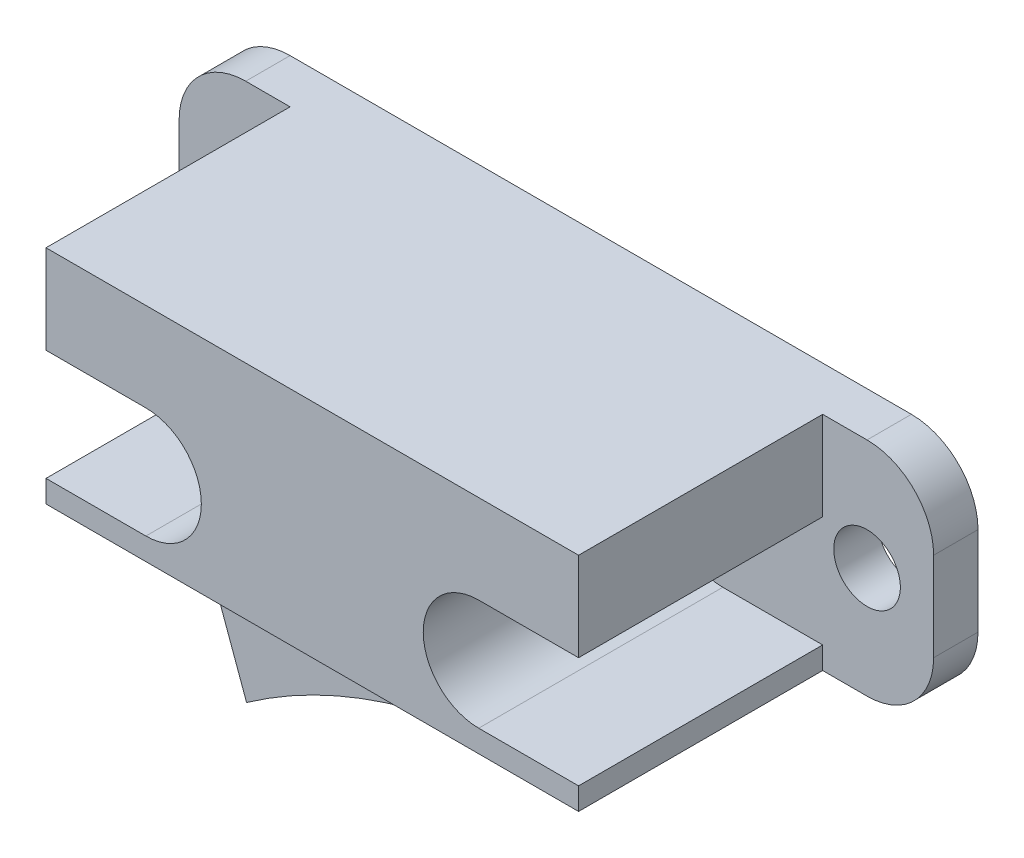
SolidWorks part; units mm, degrees
ref_plane "前视基准面" through (0, 0, 0) normal (0, 0, 1) x (1, 0, 0)
ref_plane "上视基准面" through (0, 0, 0) normal (0, 1, 0) x (1, 0, 0)
ref_plane "右视基准面" through (0, 0, 0) normal (1, 0, 0) x (0, 0, -1)
sketch "草图1" plane through (0, 0, 0) normal (0, 0, 1) x (1, 0, 0)
  line L1 (17, -5) -> (-17, -5)
  line L2 (17, -5) -> (17, 5)
  line L3 (17, 5) -> (-17, 5)
  line L4 (-17, -5) -> (-17, 5)
  line L5 (17, -5) -> (-17, 5) construction
  line L6 (17, 5) -> (-17, -5) construction
  point P0 (0, 0)
  dimension "D1" = 34
  dimension "D2" = 10
extrude "凸台-拉伸1" add sketch "草图1" along normal blind 2
fillet "圆角1" radius 3 4 edges at (17, -5, 1) (17, 5, 1) (-17, -5, 1) (-17, 5, 1)
sketch "草图2" plane through (0, 0, 2) normal (0, 0, 1) x (1, 0, 0)
  line L0 (-14, 5) -> (-14, -5) construction
  line L1 (14, 5) -> (-14, 5) construction
  line L2 (-14, -5) -> (14, -5) construction
  line L3 (0, 5) -> (0, -5) construction
  line L4 (-17, 0) -> (17, 0) construction
  line L5 (-17, 2) -> (-17, -2) construction
  line L6 (17, -2) -> (17, 2) construction
  circle A0 centre (-14, 0) radius 1.5
  circle A1 centre (14, 0) radius 1.5
  dimension "D1" = 3
  dimension "D2" = 14
extrude "切除-拉伸1" cut sketch "草图2" against normal blind 2
sketch "草图3" plane through (0, 0, 2) normal (0, 0, 1) x (1, 0, 0)
  line L0 (0, 5) -> (0, -5) construction
  line L1 (14, 5) -> (-14, 5) construction
  line L2 (-14, -5) -> (14, -5) construction
  line L3 (12, -5) -> (-12, -5)
  line L4 (-12, -5) -> (-12, -4)
  line L5 (-12, -4) -> (-7.5, -4)
  line L6 (-12, 5) -> (-12, 1)
  line L7 (-12, 1) -> (-7.5, 1)
  line L8 (-12, 5) -> (12, 5)
  line L9 (12, -5) -> (12, -4)
  line L10 (12, -4) -> (7.5, -4)
  line L11 (12, 1) -> (7.5, 1)
  line L12 (12, 5) -> (12, 1)
  arc A0 (-7.5, 1) -> (-7.5, -4) centre (-7.5, -1.5) cw
  arc A1 (7.5, 1) -> (7.5, -4) centre (7.5, -1.5) ccw
  dimension "D1" = 12
  dimension "D2" = 4.5
  dimension "D3" = 1
  dimension "D4" = 4
extrude "凸台-拉伸2" add sketch "草图3" along normal blind 11
sketch "草图5" plane through (0, -5, 0) normal (0, -1, 0) x (1, 0, 0)
  line L0 (0, 13) -> (0, 0) construction
  line L1 (-12, 13) -> (12, 13) construction
  line L2 (-12, 6) -> (12, 6) construction
  line L3 (-12, 13) -> (-12, 2) construction
  line L4 (12, 13) -> (12, 2) construction
  line L6 (10.5, -1) -> (-10.5, -1)
  line L7 (10.5, -1) -> (10.5, 13)
  line L8 (10.5, 13) -> (-10.5, 13)
  line L9 (-10.5, -1) -> (-10.5, 13)
  line L10 (10.5, -1) -> (-10.5, 13) construction
  line L11 (10.5, 13) -> (-10.5, -1) construction
  point P11 (0, 6)
  dimension "D1" = 7
  dimension "D2" = 21
  dimension "12" = 14
extrude "凸台-拉伸4" add sketch "草图5" along normal blind 2 draft 48
sketch "草图6" plane through (0, -7, 0) normal (0, -1, 0) x (1, 0, 0)
  line L0 (0, 10.7788) -> (0, 1.2212) construction
  line L1 (8.2788, 10.7788) -> (-8.2788, 10.7788) construction
  line L2 (-8.2788, 1.2212) -> (8.2788, 1.2212) construction
  line L3 (-8.2788, 6) -> (8.2788, 6) construction
  line L4 (-8.2788, 10.7788) -> (-8.2788, 1.2212) construction
  line L5 (8.2788, 1.2212) -> (8.2788, 10.7788) construction
  line L7 (7.5, 2) -> (-7.5, 2)
  line L8 (7.5, 2) -> (7.5, 10)
  line L9 (7.5, 10) -> (-7.5, 10)
  line L10 (-7.5, 2) -> (-7.5, 10)
  line L11 (7.5, 2) -> (-7.5, 10) construction
  line L12 (7.5, 10) -> (-7.5, 2) construction
  point P12 (0, 6)
  dimension "D1" = 15
  dimension "D2" = 8
extrude "切除-拉伸2" cut sketch "草图6" against normal blind 0.3
sketch "草图8" plane through (0, 0, 2) normal (0, 0, 1) x (1, 0, 0)
  line L0 (7.5, -6.7) -> (7.5, -7)
  line L1 (7.5, -6.7) -> (-7.5, -6.7)
  line L2 (-7.5, -6.7) -> (-7.5, -7)
  line L3 (-7.5, -7) -> (-6.503, -9.7392) construction
  line L4 (-7.5, -7) -> (-5.9609, -11.2286)
  arc A0 (-5.9609, -11.2286) -> (7.5, -7) centre (7.3649, -30.1093) cw
  dimension "D1" = 70
  dimension "D2" = 4.5
extrude "凸台-拉伸5" add sketch "草图8" along normal blind 8
